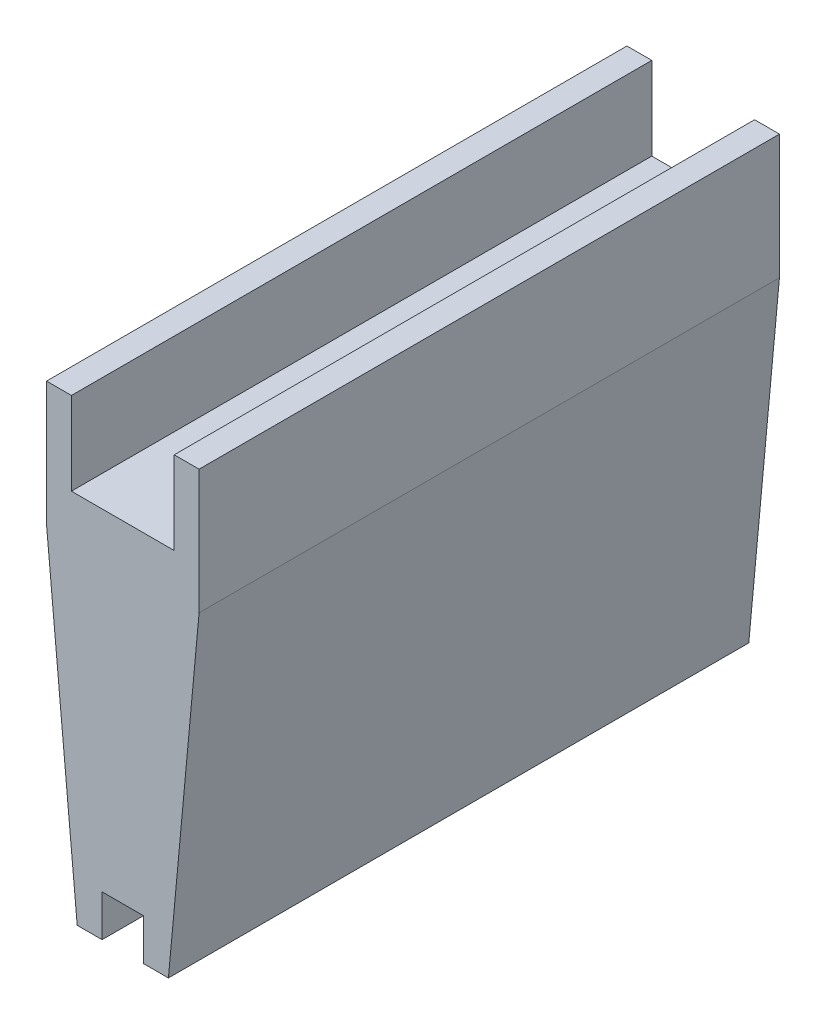
SolidWorks part; units mm, degrees
ref_plane "Front Plane" through (0, 0, 0) normal (0, 0, 1) x (1, 0, 0)
ref_plane "Top Plane" through (0, 0, 0) normal (0, 1, 0) x (1, 0, 0)
ref_plane "Right Plane" through (0, 0, 0) normal (1, 0, 0) x (0, 0, -1)
sketch "Sketch1" plane through (0, 0, 0) normal (0, 0, 1) x (1, 0, 0)
  line L0 (0, 0) -> (0, 55)
  line L1 (0, 55) -> (3, 55)
  line L2 (3, 55) -> (3, 45)
  line L3 (3, 45) -> (15.4, 45)
  line L4 (15.4, 45) -> (15.4, 55)
  line L5 (15.4, 55) -> (18.4, 55)
  line L6 (18.4, 55) -> (18.4, 0)
  line L7 (18.4, 0) -> (11.7, 0)
  line L8 (11.7, 0) -> (11.7, 5)
  line L9 (11.7, 5) -> (6.7, 5)
  line L10 (6.7, 5) -> (6.7, 0)
  line L11 (0, 0) -> (6.7, 0)
  line L12 (9.2, 45) -> (9.2, 5) construction
  dimension "D1" = 12.4
  dimension "D2" = 10
  dimension "D3" = 40
  dimension "D4" = 5
  dimension "D5" = 5
  dimension "D6" = 3
extrude "Boss-Extrude1" add sketch "Sketch1" along normal blind 70
chamfer "Chamfer1" distance 40 distance2 3.7 1 edges at (0, 0, 35)
chamfer "Chamfer2" distance 3.7 distance2 40 1 edges at (18.4, 0, 35)
